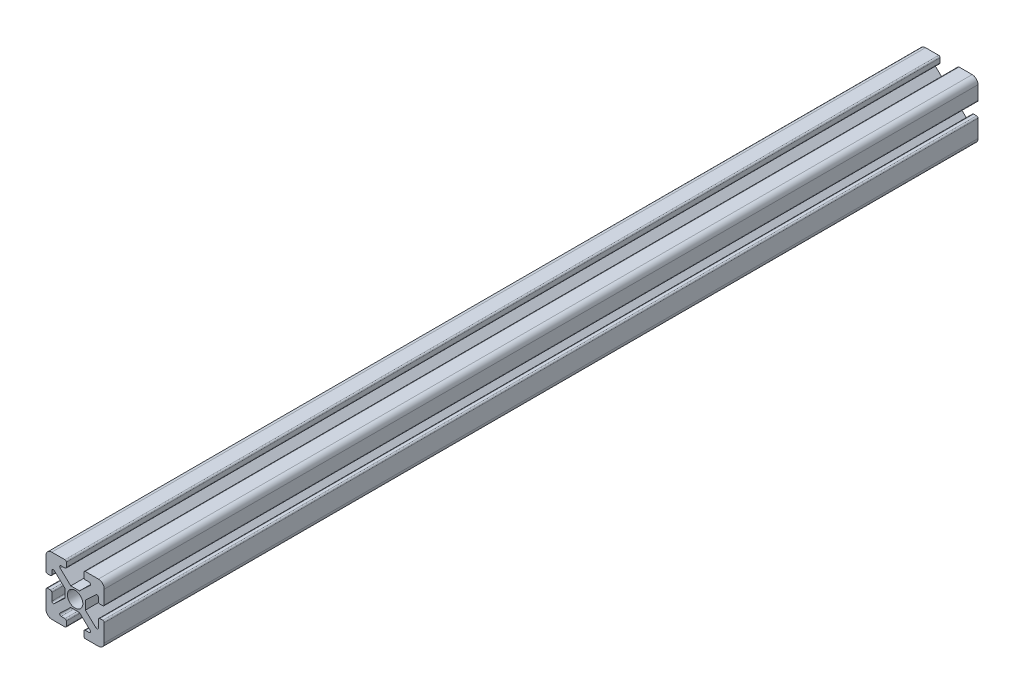
SolidWorks part; units mm, degrees
ref_plane "Front Plane" through (0, 0, 0) normal (0, 0, 1) x (1, 0, 0)
ref_plane "Top Plane" through (0, 0, 0) normal (0, 1, 0) x (1, 0, 0)
ref_plane "Right Plane" through (0, 0, 0) normal (1, 0, 0) x (0, 0, -1)
sketch "Sketch1" plane through (0, 0, 0) normal (0, 0, 1) x (1, 0, 0)
  line L0 (0, 2) -> (0, 8.0075)
  line L1 (2, 20) -> (6.5, 20)
  line L2 (20, 18) -> (20, 13.3075)
  line L3 (18, 0) -> (13.5, 0)
  line L4 (10, 0.2965) -> (10, 6.7965) construction
  line L5 (-0.015, 9.9158) -> (6.485, 9.9158) construction
  line L6 (18.5, 8.5075) -> (19.5, 8.5075)
  line L7 (18.5, 12.8075) -> (19.5, 12.8075)
  line L8 (13, 19.5) -> (13, 18.0175)
  line L9 (7, 19.5) -> (7, 18.0175)
  line L10 (2, 14.5732) -> (2, 13.3075)
  line L11 (5.2, 2.5071) -> (6.5, 2.5071)
  line L12 (18, 5.4513) -> (18, 8.0075)
  line L13 (14.8, 17.5175) -> (13.5, 17.5175)
  line L14 (1.5, 12.8075) -> (0.5, 12.8075)
  line L15 (13.5, 20) -> (18, 20)
  line L16 (6.5, 17.5175) -> (5.2, 17.5175)
  line L17 (20, 8.0075) -> (20, 2)
  line L18 (18, 13.3075) -> (18, 14.5732)
  line L19 (0, 13.3075) -> (0, 18)
  line L20 (2, 8.0075) -> (2, 5.4513)
  line L21 (6.5, 0) -> (2, 0)
  line L22 (13.5, 2.5071) -> (14.8, 2.5071)
  line L23 (1.5, 8.5075) -> (0.5, 8.5075)
  line L24 (13, 0.5) -> (13, 2.0071)
  line L25 (7, 2.0071) -> (7, 0.5)
  line L26 (17.1575, 14.9375) -> (13.515, 11.5123)
  line L27 (15.1425, 16.6533) -> (11.5, 13.228)
  line L28 (4.8575, 16.6533) -> (8.5, 13.228)
  line L29 (2.8425, 14.9375) -> (6.485, 11.5123)
  line L30 (13.515, 8.5123) -> (17.1575, 5.0871)
  line L31 (8.5, 6.7965) -> (11.5, 6.7965)
  line L32 (6.485, 8.5123) -> (6.485, 11.5123)
  line L33 (8.5, 13.228) -> (11.5, 13.228)
  line L34 (13.515, 8.5123) -> (13.515, 11.5123)
  line L37 (6.485, 8.5123) -> (2.8425, 5.0871)
  line L38 (13.515, 9.9158) -> (19.985, 9.9158) construction
  line L39 (11.5, 6.7965) -> (15.1425, 3.3713)
  line L41 (8.5, 6.7965) -> (4.8575, 3.3713)
  line L43 (10.0737, 13.228) -> (10.0737, 19.728) construction
  circle A0 centre (10, 10) radius 2.65
  arc A1 (0, 18) -> (2, 20) centre (2, 18) cw
  arc A2 (0, 2) -> (2, 0) centre (2, 2) ccw
  arc A3 (20, 2) -> (18, 0) centre (18, 2) cw
  arc A4 (18, 20) -> (20, 18) centre (18, 18) cw
  arc A5 (19.5, 8.5075) -> (20, 8.0075) centre (19.5, 8.0075) cw
  arc A6 (0.5, 8.5075) -> (0, 8.0075) centre (0.5, 8.0075) ccw
  arc A7 (0.5, 12.8075) -> (0, 13.3075) centre (0.5, 13.3075) cw
  arc A8 (13, 19.5) -> (13.5, 20) centre (13.5, 19.5) cw
  arc A9 (7, 19.5) -> (6.5, 20) centre (6.5, 19.5) ccw
  arc A10 (18, 8.0075) -> (18.5, 8.5075) centre (18.5, 8.0075) cw
  arc A11 (18.5, 12.8075) -> (18, 13.3075) centre (18.5, 13.3075) cw
  arc A12 (19.5, 12.8075) -> (20, 13.3075) centre (19.5, 13.3075) ccw
  arc A13 (7, 18.0175) -> (6.5, 17.5175) centre (6.5, 18.0175) cw
  arc A14 (13.5, 17.5175) -> (13, 18.0175) centre (13.5, 18.0175) cw
  arc A15 (2, 13.3075) -> (1.5, 12.8075) centre (1.5, 13.3075) cw
  arc A16 (2, 8.0075) -> (1.5, 8.5075) centre (1.5, 8.0075) ccw
  arc A17 (6.5, 2.5071) -> (7, 2.0071) centre (6.5, 2.0071) cw
  arc A18 (7, 0.5) -> (6.5, 0) centre (6.5, 0.5) cw
  arc A19 (13.5, 2.5071) -> (13, 2.0071) centre (13.5, 2.0071) ccw
  arc A20 (13, 0.5) -> (13.5, 0) centre (13.5, 0.5) ccw
  arc A21 (17.1575, 5.0871) -> (18, 5.4513) centre (17.5, 5.4513) ccw
  arc A22 (14.8, 2.5071) -> (15.1425, 3.3713) centre (14.8, 3.0071) ccw
  arc A23 (5.2, 2.5071) -> (4.8575, 3.3713) centre (5.2, 3.0071) cw
  arc A24 (2, 5.4513) -> (2.8425, 5.0871) centre (2.5, 5.4513) ccw
  arc A25 (2, 14.5732) -> (2.8425, 14.9375) centre (2.5, 14.5732) cw
  arc A26 (4.8575, 16.6533) -> (5.2, 17.5175) centre (5.2, 17.0175) cw
  arc A27 (17.1575, 14.9375) -> (18, 14.5732) centre (17.5, 14.5732) cw
  arc A28 (14.8, 17.5175) -> (15.1425, 16.6533) centre (14.8, 17.0175) cw
  point P13 (0, 20)
  point P16 (0, 0)
  point P19 (20, 0)
  point P42 (20, 8.5075)
  point P45 (0, 8.5075)
  point P48 (0, 12.8075)
  point P51 (13, 20)
  point P64 (2, 12.8075)
  point P67 (2, 8.5075)
  point P70 (7, 2.5071)
  point P75 (13, 2.5071)
  dimension "D3" = 2
  dimension "D8" = 0.5
  dimension "D4" = 0.5
  dimension "D5" = 0.5
  dimension "D6" = 0.5
  dimension "D7" = 0.5
  dimension "D9" = 5.3
  dimension "D12" = 2
  dimension "D13" = 5
  dimension "D14" = 1.3
  dimension "D1" = 20
  dimension "D2" = 20
  dimension "D10" = 3
  dimension "D11" = 2
  dimension "D15" = 1.3
  dimension "D16" = 1.3
  dimension "D17" = 6
  dimension "D18" = 5.3
  dimension "D19" = 10
  dimension "D20" = 10
  dimension "D21" = 133.239
extrude "Boss-Extrude2" add sketch "Sketch1" along normal blind 300
